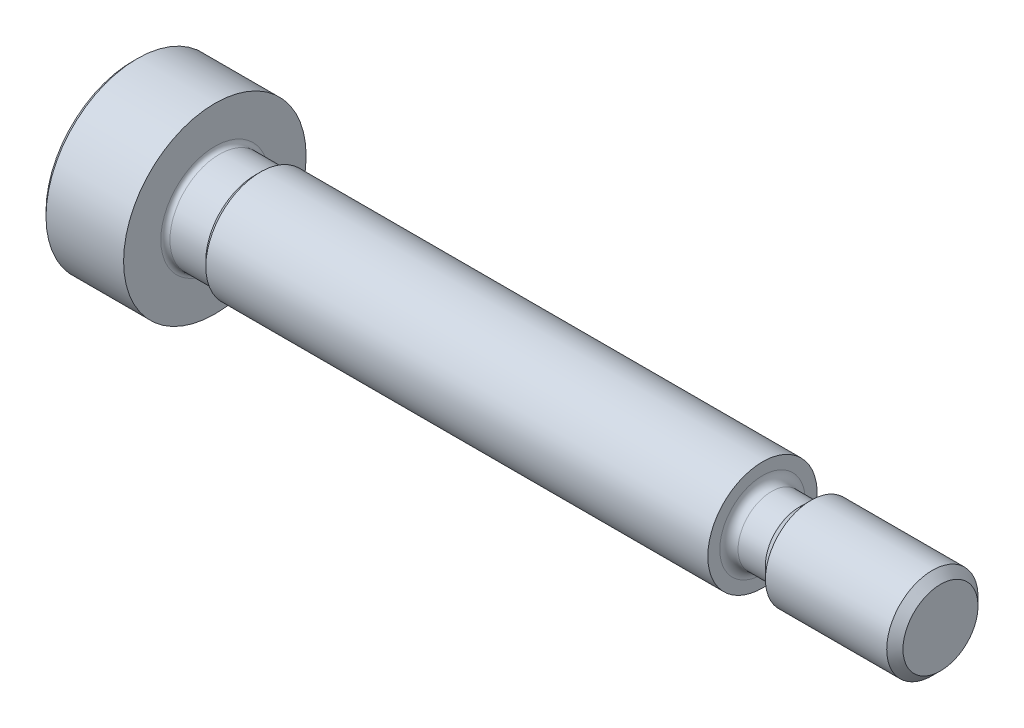
SolidWorks part; units mm, degrees
ref_plane "Plane1" through (0, 0, 0) normal (0, 0, 1) x (1, 0, 0)
ref_plane "Plane2" through (0, 0, 0) normal (0, 1, 0) x (1, 0, 0)
ref_plane "Plane3" through (0, 0, 0) normal (1, 0, 0) x (0, 0, -1)
sketch "BodySke" plane through (0, 0, 0) normal (0, 0, 1) x (1, 0, 0)
  line L0 (0, 0) -> (0, 5)
  line L2 (0, 5) -> (4.5, 5)
  line L3 (4.5, 5) -> (4.5, 2.96)
  line L4 (4.75, 2.71) -> (6.715, 2.71)
  line L5 (6.715, 2.71) -> (7, 2.995)
  line L6 (7, 2.995) -> (34.5, 2.995)
  line L7 (34.5, 2.995) -> (34.5, 2.34)
  line L8 (35, 1.84) -> (36.5, 1.84)
  line L9 (36.5, 1.84) -> (37.16, 2.5)
  line L10 (37.16, 2.5) -> (43.805, 2.5)
  line L11 (43.805, 2.5) -> (44.25, 2.055)
  line L12 (44.25, 2.055) -> (44.25, 0)
  line L13 (44.25, 0) -> (0, 0)
  line L14 (-6.35, 0) -> (107.95, 0) construction
  line L15 (43.805, -2.5) -> (44.25, -2.055) construction
  line L16 (34.5, -1.84) -> (36.5, -1.84) construction
  line L17 (7, -2.995) -> (34.5, -2.995) construction
  line L18 (4.5, -2.71) -> (6.715, -2.71) construction
  line L20 (37.3, 6.6914) -> (37.3, -10.6614) construction
  line L21 (34.5, 5.8311) -> (34.5, -10.0185) construction
  arc A0 (34.5, 2.34) -> (35, 1.84) centre (35, 2.34) ccw
  arc A1 (4.75, 2.71) -> (4.5, 2.96) centre (4.75, 2.96) cw
  point P29 (34.5, 1.84)
  point P32 (4.5, 2.71)
  dimension "Thread_neck_fillet_rad" = 0.5
  dimension "Head_fillet_radius" = 0.25
  dimension "Head_ht" = 4.5
  dimension "Shoulder_neck_dia" = 5.42
  dimension "Diameter" = 5.99
  dimension "Thread_dia" = 5
  dimension "Minor_dia" = 4.11
  dimension "Thread_ch_ang" = 45
  dimension "Thread_neck_dia" = 3.68
  dimension "D11" = 45
  dimension "Thread_length" = 9.75
  dimension "D13" = 45
  dimension "Length" = 30
  dimension "Thread_neck_width" = 2
  dimension "Shoulder_neck_width" = 2.5
  dimension "Thread_nom" = 9.75
  dimension "Advance" = 0.8
  dimension "Thread_lim" = 6.95
  dimension "Head_dia" = 10
revolve "BaseBody" add sketch "BodySke" angle 360 about L14
cosmetic thread "ThreadCosmetic" parameters "Thread_length"=6.95, "Thread_minor"=4.11
chamfer "Chamfer1" distance 0.25 1 edges at (0, 0, 5)
sketch "Sketch2" plane through (0, 0, 0) normal (0, 0, 1) x (1, 0, 0)
  line L0 (0, 1.54) -> (2.4, 1.54)
  line L1 (2.4, 1.54) -> (3.2891, 0)
  line L3 (3.2891, 0) -> (0, 0)
  line L4 (0, 0) -> (0, 1.54)
  line L5 (0, -1.54) -> (2.4, -1.54) construction
  line L6 (0, 0) -> (47.625, 0) construction
  dimension "D2" = 60
  dimension "PreBroach_depth" = 2.4
  dimension "PreBroach_dia" = 3.08
revolve "PreBroach" cut sketch "Sketch2" angle 360 about L6
sketch "Sketch3" plane through (0, 0, 0) normal (-1, 0, 0) x (0, 0, 1)
  line L0 (-1.54, -0.8891) -> (-1.54, 0.8891)
  line L1 (-1.54, 0.8891) -> (0, 1.7782)
  line L2 (0, 1.7782) -> (1.54, 0.8891)
  line L3 (1.54, 0.8891) -> (1.54, -0.8891)
  line L4 (1.54, -0.8891) -> (0, -1.7782)
  line L5 (0, -1.7782) -> (-1.54, -0.8891)
  dimension "Hex_size" = 3.08
  dimension "D1" = 1.54
  dimension "D2" = 1.54
  dimension "D3" = 120
  dimension "D4" = 3.08
extrude "Hex" cut sketch "Sketch3" against normal blind 2.4
sketch "ThdSchSke" plane through (0, 0, 0) normal (0, 0, 1) x (1, 0, 0)
  line L0 (37.3, -2.055) -> (36.6418, -2.995)
  line L1 (37.3, -2.055) -> (37.9582, -2.995)
  line L2 (37.9582, -2.995) -> (37.9582, -3.7437)
  line L3 (-3.175, 0) -> (5.1513, 0) construction
  line L5 (37.9582, -3.7437) -> (36.6418, -3.7437)
  line L6 (36.6418, -3.7437) -> (36.6418, -2.995)
  dimension "Thread_minor" = 4.11
  dimension "Diameter" = 5.99
  dimension "SideAngle" = 55
  dimension "VeeAngle" = 70
  dimension "Overcut" = 7.4875
  dimension "Start" = 37.3
revolve "ThreadSchematic" [suppressed] cut sketch "ThdSchSke" angle 360 about L3
pattern_linear "ThdSchPat" [suppressed]
equation "\"Thread_minor@ThreadCosmetic\" = \"Minor_dia@BodySke\""
equation "\"D1@Sketch3\" = \"Hex_size@Sketch3\" / 2"
equation "\"D2@Sketch3\" = \"D1@Sketch3\""
equation "\"D4@Sketch3\" = \"Hex_size@Sketch3\""
equation "\"Width@Chamfer1\" = \"Head_fillet_radius@BodySke\""
equation "\"Thread_length@ThreadCosmetic\" = ((sgn( (\"Thread_length@BodySke\" - \"Advance@BodySke\" - \"Thread_neck_width@BodySke\" ) - \"Thread_nom@BodySke\" )-1)*( (\"Thread_length@BodySke\" - \"Advance@BodySke\" - \"Thread_neck_width@BodySke\" ) - \"Thread_nom@BodySke\" ))/-2+ \"Thread_nom@BodySke\""
equation "\"Thread_minor@ThdSchSke\" = \"Minor_dia@BodySke\""
equation "\"Diameter@ThdSchSke\" = \"Diameter@BodySke\""
equation "\"Overcut@ThdSchSke\" = \"Diameter@BodySke\" * 1.25"
equation "\"Start@ThdSchSke\" = \"Head_ht@BodySke\" + \"Length@BodySke\" + \"Thread_length@BodySke\" -  \"Thread_length@ThreadCosmetic\"  '---Non-countersunk---"
equation "\"Num_threads@ThdSchPat\" = int( \"Thread_length@ThreadCosmetic\" / \"Advance@BodySke\" + 0.999 ) + 1"
equation "\"Advance@ThdSchPat\" = \"Thread_length@ThreadCosmetic\" /  (\"Num_threads@ThdSchPat\" - 1) 'relax it"
equation "\"Num_threads@ThdSchPat\" = \"Num_threads@ThdSchPat\" - sgn( \"Num_threads@ThdSchPat\" - 1) '---chamfered tips only---"
